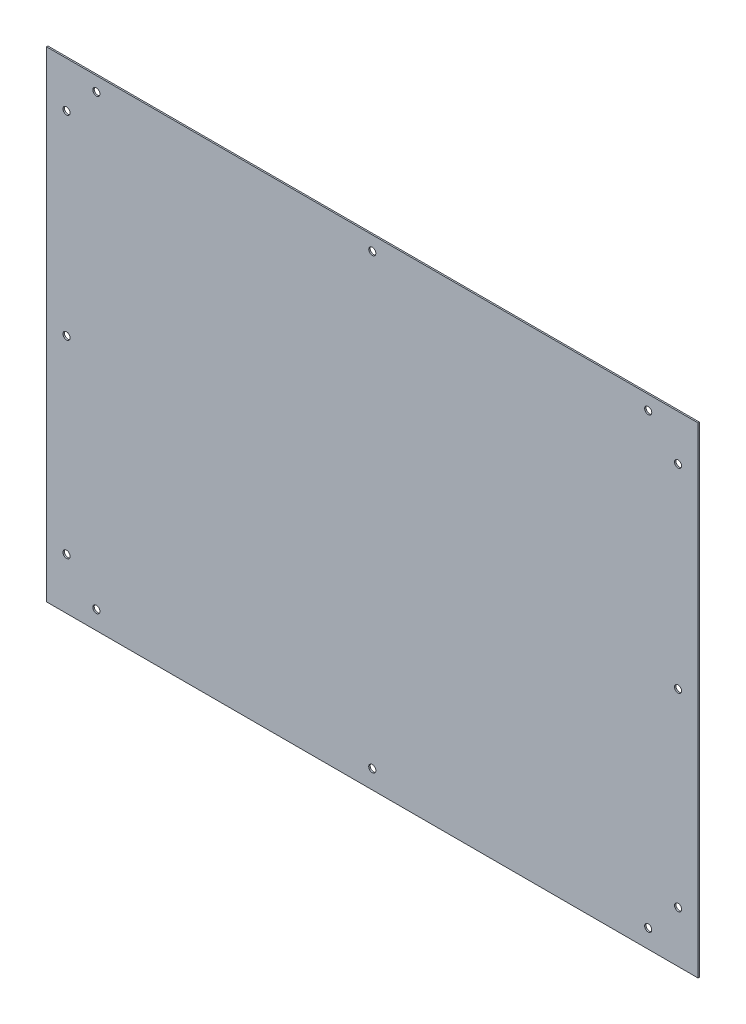
SolidWorks part; units mm, degrees
material "1345 Alloy"
ref_plane "Front Plane" through (0, 0, 0) normal (0, 0, 1) x (1, 0, 0)
ref_plane "Top Plane" through (0, 0, 0) normal (0, 1, 0) x (1, 0, 0)
ref_plane "Right Plane" through (0, 0, 0) normal (1, 0, 0) x (0, 0, -1)
sketch "Sketch1" plane through (0, 0, 0) normal (0, 0, 1) x (1, 0, 0)
  line L1 (-229, 169) -> (229, 169)
  line L2 (-229, 169) -> (-229, -169)
  line L3 (-229, -169) -> (229, -169)
  line L4 (229, 169) -> (229, -169)
  line L5 (-229, 169) -> (229, -169) construction
  line L6 (-229, -169) -> (229, 169) construction
  point P0 (0, 0)
  dimension "D1" = 458
  dimension "D2" = 338
extrude "Boss-Extrude1" add sketch "Sketch1" along normal blind 1
sketch "Sketch2" plane through (0, 0, 1) normal (0, 0, 1) x (1, 0, 0)
  line L4 (-194.0026, -156) -> (193.9974, -156) construction
  line L5 (-215, 137) -> (-215, -133) construction
  line L6 (215, 137) -> (215, -133) construction
  line L8 (194, 159) -> (194, 169) construction
  line L11 (-229, -169) -> (229, -169) construction
  line L12 (229, 0) -> (215, 0) construction
  line L14 (229, 169) -> (-229, 169) construction
  circle A0 centre (-194, 159) radius 2.5
  circle A1 centre (-194.0026, -156) radius 2.5
  circle A2 centre (193.9974, -156) radius 2.5
  circle A3 centre (194, 159) radius 2.5
  circle A4 centre (-215, 0) radius 2.5
  circle A5 centre (-215, -133) radius 2.5
  circle A6 centre (-215, 137) radius 2.5
  circle A7 centre (215, 0) radius 2.5
  circle A8 centre (215, -133) radius 2.5
  circle A9 centre (215, 137) radius 2.5
  circle A10 centre (0, 159) radius 2.5
  circle A11 centre (-0.0026, -156) radius 2.5
  dimension "D3" = 5
  dimension "D6" = 5
  dimension "D7" = 5
  dimension "D8" = 5
  dimension "D13" = 5
  dimension "D14" = 5
  dimension "D15" = 5
  dimension "D19" = 5
  dimension "D20" = 5
  dimension "D4" = 215
  dimension "D5" = 215
  dimension "D9" = 13
  dimension "D11" = 36
  dimension "D18" = 13
  dimension "D21" = 194
  dimension "D24" = 194
  dimension "D26" = 32
  dimension "D27" = 137
extrude "Cut-Extrude1" cut sketch "Sketch2" against normal through all
